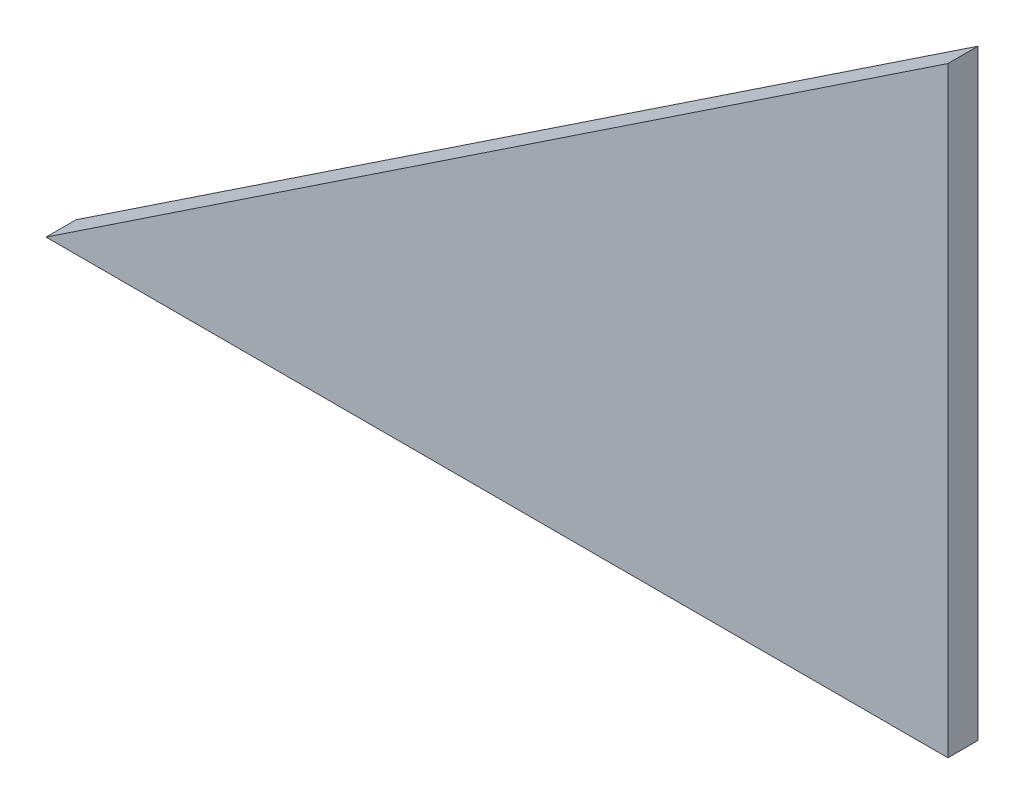
SolidWorks part; units mm, degrees
material "1060 Alloy"
ref_plane "Front Plane" through (0, 0, 0) normal (0, 0, 1) x (1, 0, 0)
ref_plane "Top Plane" through (0, 0, 0) normal (0, 1, 0) x (1, 0, 0)
ref_plane "Right Plane" through (0, 0, 0) normal (1, 0, 0) x (0, 0, -1)
sketch "Sketch1" plane through (0, 0, 23.6765) normal (0, 0, -1) x (-1, 0, 0)
  line L0 (-196.8096, 11.9601) -> (-196.8096, 37.3601)
  line L1 (-196.8096, 11.9601) -> (-6.3096, 11.9601) construction
  line L2 (-196.8096, 13.2301) -> (-196.8096, 54.5051) construction
  line L3 (-196.8096, 37.3601) -> (-158.7096, 11.9601)
  line L4 (-158.7096, 11.9601) -> (-196.8096, 11.9601)
  dimension "D1" = 25.4
  dimension "D2" = 38.1
extrude "Boss-Extrude1" add sketch "Sketch1" along normal blind 1.27
